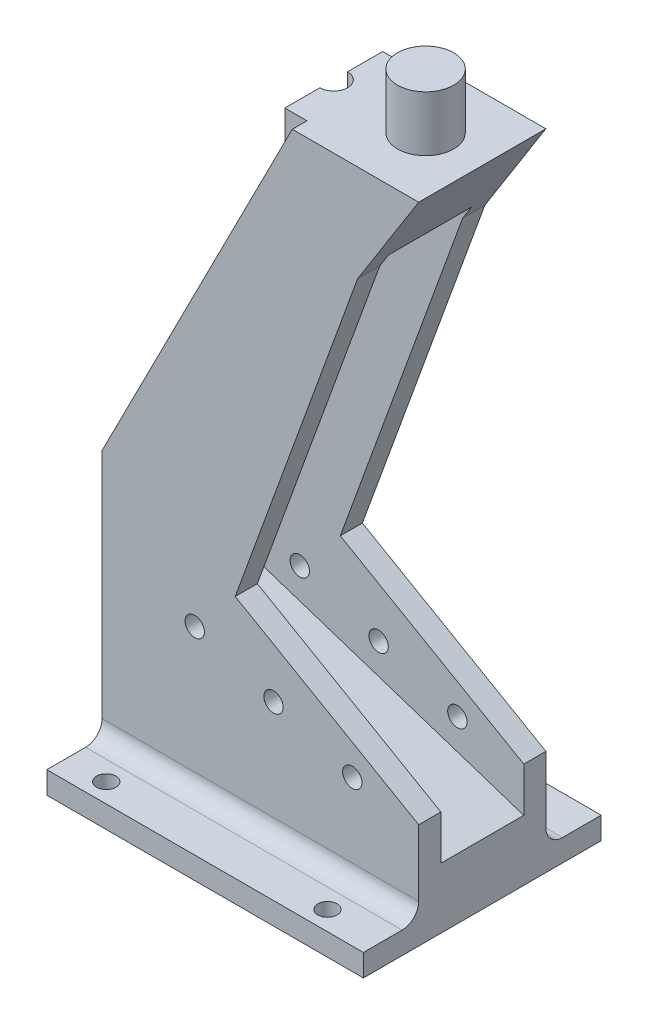
SolidWorks part; units mm, degrees
ref_plane "Front Plane" through (0, 0, 0) normal (0, 0, 1) x (1, 0, 0)
ref_plane "Top Plane" through (0, 0, 0) normal (0, 1, 0) x (1, 0, 0)
ref_plane "Right Plane" through (0, 0, 0) normal (1, 0, 0) x (0, 0, -1)
sketch "Sketch1" plane through (0, 0, 0) normal (0, 0, 1) x (1, 0, 0)
  line L0 (0, 0) -> (57.2501, 0)
  line L1 (57.2501, 0) -> (57.2501, 15)
  line L2 (57.2501, 15) -> (24.066, 34.1588)
  line L3 (24.066, 34.1588) -> (46.2104, 95)
  line L4 (46.2104, 95) -> (57.2501, 112.5)
  line L5 (57.2501, 112.5) -> (52.2501, 112.5)
  line L6 (18.5033, 81.3148) -> (0, 45)
  line L7 (0, 45) -> (0, 0)
  line L8 (57.2501, 112.5) -> (57.2501, 7.5) construction
  line L9 (57.2501, 7.5) -> (5, 24.6736) construction
  line L10 (5, 24.6736) -> (5, 29.6736) construction
  line L11 (5, 29.6736) -> (57.2501, 112.5) construction
  line L12 (52.2501, 112.5) -> (18.5033, 81.3148)
  line L13 (52.2501, 112.5) -> (34.393, 112.5) construction
  line L14 (34.393, 112.5) -> (18.5033, 81.3148) construction
  line L15 (18.5033, 81.3148) -> (34.393, 112.5)
  line L16 (34.393, 112.5) -> (52.2501, 112.5)
  dimension "D2" = 5
  dimension "D3" = 30
  dimension "D4" = 70
  dimension "D5" = 63
  dimension "D6" = 45
  dimension "D7" = 105
  dimension "D8" = 97.93
  dimension "D9" = 5
  dimension "D10" = 55
  dimension "D11" = 35
  dimension "D12" = 15
  dimension "D13" = 80
  dimension "D14" = 5
extrude "Boss-Extrude1" add sketch "Sketch1" along normal mid plane 23 contours L16 L15 L12
sketch "Sketch2" plane through (0, 0, 0) normal (0, 0, 1) x (1, 0, 0)
  line L0 (21.7429, 78.8621) -> (4, 44.0397)
  line L1 (4, 44.0397) -> (4, 24.4759)
  line L2 (5, 29.6736) -> (57.2501, 112.5) construction
  line L5 (47.7875, 97.5) -> (57.2501, 112.5)
  line L11 (57.2501, 0) -> (57.2501, 15) construction
  line L12 (4, 24.4759) -> (57.2501, 6.9737)
  line L14 (47.7875, 97.5) -> (47.7875, 102.9298)
  line L18 (57.2501, 112.5) -> (52.2501, 112.5) construction
  line L19 (46.2104, 95) -> (57.2501, 112.5) construction
  line L22 (0, 0) -> (57.2501, 0) construction
  line L23 (0, 45) -> (0, 0)
  line L24 (0, 0) -> (57.2501, 0)
  line L27 (57.2501, 6.9737) -> (57.2501, 0)
  line L31 (57.2501, 7.5) -> (5, 24.6736) construction
  line L32 (18.5033, 81.3148) -> (34.393, 112.5)
  line L33 (21.7429, 78.8621) -> (47.7875, 102.9298)
  line L34 (52.2501, 112.5) -> (18.5033, 81.3148) construction
  line L35 (18.5033, 81.3148) -> (0, 45) construction
  line L36 (52.2501, 112.5) -> (18.5033, 81.3148)
  line L37 (18.5033, 81.3148) -> (0, 45)
  line L38 (57.2501, 112.5) -> (52.2501, 112.5)
  line L39 (34.393, 112.5) -> (52.2501, 112.5)
  dimension "D1" = 4
  dimension "D2" = 15
  dimension "D3" = 4
  dimension "D4" = 4
  dimension "D5" = 0.5
extrude "Cut-Extrude2" cut sketch "Sketch2" against normal mid plane 15 flip side to cut
sketch "Sketch4" plane through (0, 0, 11.5) normal (0, 0, 1) x (1, 0, 0)
  line L1 (5, 29.6736) -> (57.2501, 12.5) construction
  line L2 (57.2501, 0) -> (57.2501, 15) construction
  line L3 (57.2501, 7.5) -> (5, 24.6736) construction
  circle A0 centre (45.2501, 16.4442) radius 1.75
  circle A1 centre (31, 21.1279) radius 1.75
  circle A2 centre (16.75, 25.8116) radius 1.75
  dimension "D4" = 3.5
  dimension "D1" = 12
  dimension "D2" = 15
  dimension "D3" = 15
extrude "Cut-Extrude3" cut sketch "Sketch4" against normal through all both and the other way through all
sketch "Sketch5" plane through (0, 0, 0) normal (0, -1, 0) x (1, 0, 0)
  line L0 (0, 11.5) -> (57.2501, -11.5) construction
  line L2 (0, 21.5) -> (57.2501, 21.5)
  line L3 (0, 21.5) -> (0, -21.5)
  line L4 (0, -21.5) -> (57.2501, -21.5)
  line L5 (57.2501, 21.5) -> (57.2501, -21.5)
  line L6 (0, 21.5) -> (57.2501, -21.5) construction
  line L7 (0, -21.5) -> (57.2501, 21.5) construction
  line L8 (57.2501, 11.5) -> (57.2501, -11.5) construction
  line L9 (0, 11.5) -> (57.2501, 11.5) construction
  point P4 (28.625, 0)
  dimension "D1" = 10
extrude "Boss-Extrude2" add sketch "Sketch5" along normal blind 4
sketch "Sketch6" plane through (0, 0, 0) normal (0, 1, 0) x (1, 0, 0)
  line L0 (0, 18) -> (57.2501, 18) construction
  line L3 (0, 11.5) -> (0, 21.5) construction
  line L4 (57.2501, 21.5) -> (57.2501, 11.5) construction
  circle A1 centre (7.2501, 18) radius 1.75
  circle A2 centre (47.2501, 18) radius 1.75
  dimension "D1" = 40
  dimension "D2" = 3.5
  dimension "D3" = 10
  dimension "D4" = 18
extrude "Cut-Extrude4" cut sketch "Sketch6" against normal through all both and the other way through all
mirror "Mirror5" about plane through (0, 0, 0) normal (0, 0, 1) of "Cut-Extrude4"
fillet "Fillet1" radius 3 2 edges at (28.625, 0, -11.5) (28.625, 0, 11.5)
sketch "Sketch7" plane through (0, 112.5, 0) normal (0, 1, 0) x (1, 0, 0)
  line L0 (34.393, -11.5) -> (34.393, 11.5) construction
  circle A0 centre (47.0001, 0) radius 5.08
  point P5 (34.393, 0)
  dimension "D1" = 10.16
extrude "Boss-Extrude3" add sketch "Sketch7" along normal blind 10
sketch "Sketch11" plane through (0, 112.5, 0) normal (0, 1, 0) x (1, 0, 0)
  line L5 (34.393, -11.5) -> (34.393, 11.5) construction
  line L6 (34.393, 8.85) -> (21.393, 8.85)
  line L7 (34.393, 8.85) -> (34.393, -8.85)
  line L8 (34.393, -8.85) -> (21.393, -8.85)
  line L9 (21.393, 8.85) -> (21.393, -8.85)
  line L10 (0, 11.5) -> (34.393, 11.5) construction
  line L11 (0, -11.5) -> (34.393, -11.5) construction
  dimension "D1" = 2.65
  dimension "D2" = 2.65
  dimension "D3" = 13
extrude "Cut-Extrude7" cut sketch "Sketch11" against normal blind 20
sketch "Sketch8" plane through (0, 0, 0) normal (0, 0, 1) x (1, 0, 0)
  line L6 (34.393, 112.5) -> (30.393, 112.5)
  line L7 (34.393, 112.5) -> (34.393, 99.8)
  line L8 (34.393, 99.8) -> (30.393, 99.8)
  line L9 (30.393, 112.5) -> (30.393, 99.8)
  point P6 (0, 0)
  dimension "D1" = 12.7
  dimension "D2" = 4
extrude "Boss-Extrude4" add sketch "Sketch8" along normal mid plane 17.7
sketch "Sketch9" plane through (47.0303, 99.8, 0) normal (0, -1, 0) x (-1, 0, 0)
  line L1 (16.6373, -8.85) -> (16.6373, 8.85) construction
  circle A0 centre (16.6373, 0) radius 2.5
  point P4 (0, 0)
  dimension "D1" = 5
extrude "Cut-Extrude5" cut sketch "Sketch9" against normal through all
sketch "Sketch10" plane through (30.393, -1.4317, 0) normal (-1, 0, 0) x (0, 0, 1)
  line L1 (-2.5, 101.2317) -> (-8.85, 101.2317) construction
  line L4 (8.85, 101.2317) -> (2.5, 101.2317) construction
  line L5 (-2.5, 101.2317) -> (-2.5, 113.9317) construction
  circle A0 centre (-5.675, 107.5817) radius 1.5
  circle A1 centre (5.675, 107.5817) radius 1.5
  point P7 (0, 0)
  point P13 (0, 0)
  point P14 (0, 0)
  point P15 (0, 0)
  point P19 (-5.675, 101.2317)
  point P20 (0, 0)
  point P23 (5.675, 101.2317)
  point P24 (0, 0)
  point P25 (0, 0)
  point P28 (-2.5, 107.5817)
  dimension "D1" = 3
  dimension "D2" = 3
extrude "Cut-Extrude6" cut sketch "Sketch10" against normal up to surface (4 mm away) contours A0 | A1 up to face at (34.393, 96.15, 0)
equation "\"D3@Sketch4\"=\"D2@Sketch4\""
